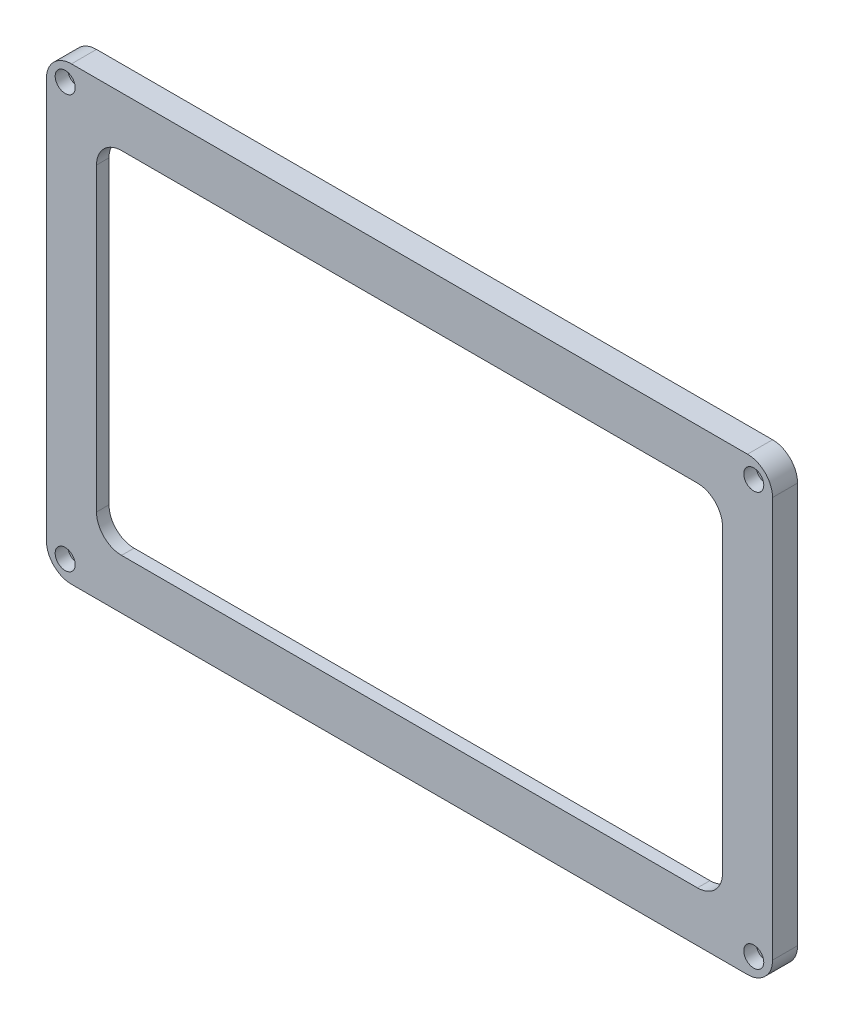
SolidWorks part; units mm, degrees
material "3.0205 (EN-AW 1200)"
ref_plane "前视基准面" through (0, 0, 0) normal (0, 0, 1) x (1, 0, 0)
ref_plane "上视基准面" through (0, 0, 0) normal (0, 1, 0) x (1, 0, 0)
ref_plane "右视基准面" through (0, 0, 0) normal (1, 0, 0) x (0, 0, -1)
sketch "草图1" plane through (0, 0, 0) normal (0, 0, 1) x (1, 0, 0)
  line L1 (-29, -18) -> (29, -18)
  line L2 (-29, -18) -> (-29, 18)
  line L3 (-29, 18) -> (29, 18)
  line L4 (29, -18) -> (29, 18)
  line L5 (-29, -18) -> (29, 18) construction
  line L6 (-29, 18) -> (29, -18) construction
  point P0 (0, 0)
  dimension "D1" = 58
  dimension "D2" = 36
extrude "凸台-拉伸1" add sketch "草图1" along normal blind 3
sketch "草图2" plane through (0, 0, 0) normal (0, 0, -1) x (-1, 0, 0)
  line L1 (-26.25, -15.25) -> (26.25, -15.25)
  line L2 (-26.25, -15.25) -> (-26.25, 15.25)
  line L3 (-26.25, 15.25) -> (26.25, 15.25)
  line L4 (26.25, -15.25) -> (26.25, 15.25)
  line L5 (-26.25, -15.25) -> (26.25, 15.25) construction
  line L6 (-26.25, 15.25) -> (26.25, -15.25) construction
  point P0 (0, 0)
  dimension "D1" = 52.5
  dimension "D2" = 30.5
extrude "切除-拉伸1" cut sketch "草图2" against normal blind 2
sketch "草图3" plane through (0, 0, 3) normal (0, 0, 1) x (1, 0, 0)
  line L1 (-25, -14) -> (25, -14)
  line L2 (-25, -14) -> (-25, 14)
  line L3 (-25, 14) -> (25, 14)
  line L4 (25, -14) -> (25, 14)
  line L5 (-25, -14) -> (25, 14) construction
  line L6 (-25, 14) -> (25, -14) construction
  point P0 (0, 0)
  dimension "D1" = 50
  dimension "D2" = 28
extrude "切除-拉伸2" cut sketch "草图3" against normal blind 2
fillet "圆角1" radius 2 8 edges at (-25, -14, 2.5) (25, -14, 2.5) (25, 14, 2.5) (-25, 14, 2.5) (-29, 18, 1.5) (29, 18, 1.5) (29, -18, 1.5) (-29, -18, 1.5)
sketch "草图4" plane through (0, 0, 0) normal (0, 0, -1) x (-1, 0, 0)
  line L1 (-29, -18) -> (29, -18)
  line L2 (-29, -18) -> (-29, 18)
  line L3 (-29, 18) -> (29, 18)
  line L4 (29, -18) -> (29, 18)
  line L5 (-29, -18) -> (29, 18) construction
  line L6 (-29, 18) -> (29, -18) construction
  point P0 (0, 0)
extrude "切除-拉伸3" cut sketch "草图4" against normal blind 1
fillet "圆角2" radius 0.2 4 edges at (26.25, 15.25, 1.5) (-26.25, 15.25, 1.5) (-26.25, -15.25, 1.5) (26.25, -15.25, 1.5)
sketch "草图5" plane through (0, 0, 3) normal (0, 0, 1) x (1, 0, 0)
  line L1 (-27.5, -16.5) -> (27.5, -16.5) construction
  line L2 (-27.5, -16.5) -> (-27.5, 16.5) construction
  line L3 (-27.5, 16.5) -> (27.5, 16.5) construction
  line L4 (27.5, -16.5) -> (27.5, 16.5) construction
  line L5 (-27.5, -16.5) -> (27.5, 16.5) construction
  line L6 (-27.5, 16.5) -> (27.5, -16.5) construction
  circle A0 centre (-27.5, 16.5) radius 0.8
  circle A1 centre (27.5, 16.5) radius 0.8
  circle A2 centre (27.5, -16.5) radius 0.8
  circle A3 centre (-27.5, -16.5) radius 0.8
  point P0 (0, 0)
  dimension "D3" = 1.6
  dimension "D1" = 55
  dimension "D2" = 33
extrude "切除-拉伸4" cut sketch "草图5" against normal blind 1
sketch "草图6" plane through (0, 0, 2) normal (0, 0, 1) x (1, 0, 0)
  circle A0 centre (-27.5, 16.5) radius 0.6
  circle A1 centre (27.5, 16.5) radius 0.6
  circle A2 centre (27.5, -16.5) radius 0.6
  circle A3 centre (-27.5, -16.5) radius 0.6
  dimension "D1" = 1.2
extrude "切除-拉伸5" cut sketch "草图6" against normal blind 20.5
